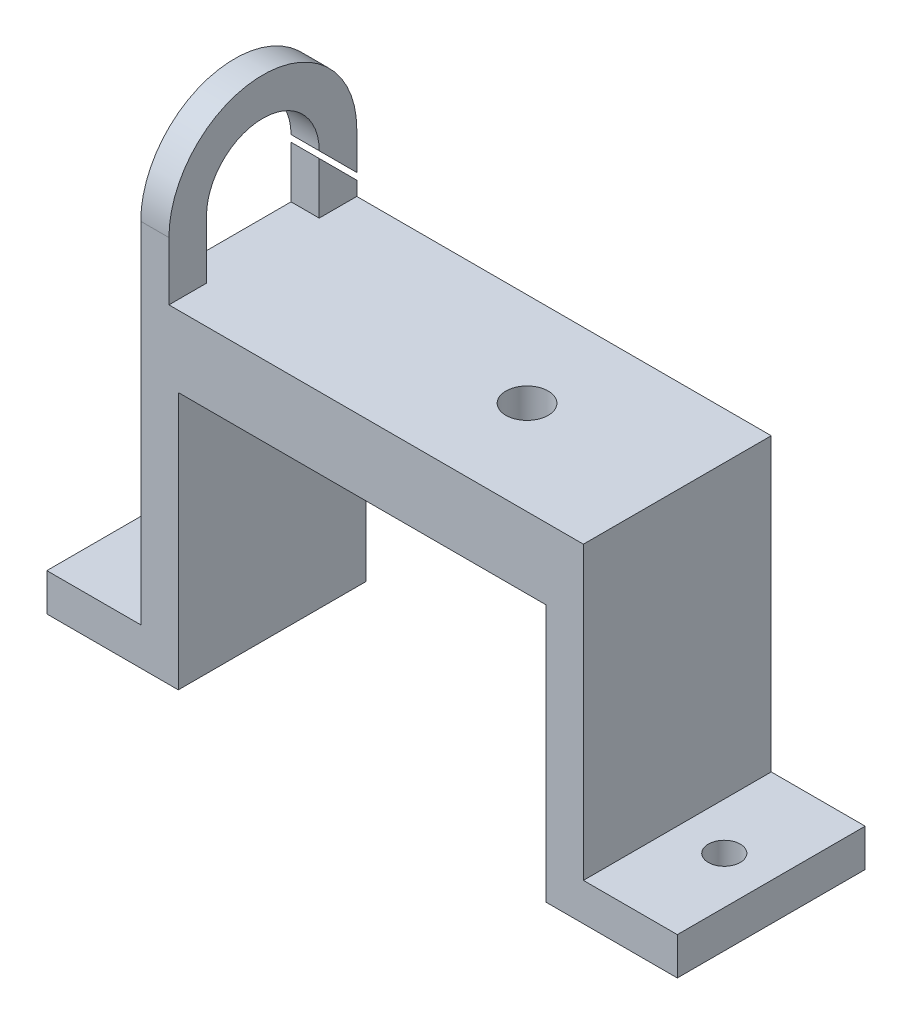
SolidWorks part; units mm, degrees
material "Onyx w/ CF"
ref_plane "Front Plane" through (0, 0, 0) normal (0, 0, 1) x (1, 0, 0)
ref_plane "Top Plane" through (0, 0, 0) normal (0, 1, 0) x (1, 0, 0)
ref_plane "Right Plane" through (0, 0, 0) normal (1, 0, 0) x (0, 0, -1)
sketch "Sketch1" plane through (0, 0, 0) normal (0, 0, 1) x (1, 0, 0)
  line L0 (-19.5635, 0) -> (19.5635, 0)
  line L1 (-19.5635, 0) -> (-19.5635, -31)
  line L2 (19.5635, 0) -> (19.5635, -31)
  line L3 (-19.5635, -31) -> (-33.5635, -31)
  line L4 (-33.5635, -31) -> (-33.5635, -27)
  line L5 (-33.5635, -27) -> (-23.5635, -27)
  line L6 (-23.5635, -27) -> (-23.5635, 4)
  line L7 (-23.5635, 4) -> (23.5635, 4)
  line L8 (23.5635, 4) -> (23.5635, -27)
  line L9 (23.5635, -27) -> (33.5635, -27)
  line L10 (33.5635, -27) -> (33.5635, -31)
  line L11 (33.5635, -31) -> (19.5635, -31)
  point P3 (0, 0)
  dimension "D1" = 39.127
  dimension "D2" = 31
  dimension "D3" = 4
  dimension "D4" = 4
  dimension "D5" = 10
  dimension "D6" = 4
extrude "Boss-Extrude1" add sketch "Sketch1" along normal mid plane 20
sketch "Sketch2" plane through (0, 0, 0) normal (1, 0, 0) x (0, 0, -1)
  line L0 (-10, 0) -> (10, 0) construction
  line L1 (-10, 4) -> (-10, -27) construction
  line L2 (10, 4) -> (10, -27) construction
  line L3 (-10, 0) -> (10, 0)
  line L4 (10, -3.5819) -> (10, 0)
  line L5 (-10, -3.5819) -> (-10, 0)
  arc A0 (-10, -3.5819) -> (10, -3.5819) centre (0, -15.75) cw
  dimension "D1" = 15.75
extrude "Boss-Extrude2" add sketch "Sketch2" along normal up to surface (39.127 mm away) from surface at -19.5635 contours L5 A0 L3 | L3 A0 L4 up to face at (19.5635, -15.5, 0) starting at face at (-19.5635, -15.5, 0)
hole_wizard "M3 Clearance Hole1" positions "Sketch3" profile "Sketch4" hole size "M3" standard "ANSI Metric"
sketch "Sketch3" plane through (0, -27, 0) normal (0, 1, 0) x (1, 0, 0)
  line L0 (-23.5635, 10) -> (-33.5635, 10) construction
  line L1 (33.5635, 10) -> (23.5635, 10) construction
  line L2 (33.5635, -10) -> (33.5635, 10) construction
  point P0 (28.5635, 0)
  point P2 (28.5635, 0)
  point P4 (-28.5635, 0)
  point P9 (-28.5635, 10)
  point P12 (28.5635, 10)
  point P15 (33.5635, 0)
sketch "Sketch4" plane through (28.5635, -27, 0) normal (1, 0, 0) x (0, 0, 1)
  line L0 (0, 0) -> (0, 8.5215)
  line L1 (0, 8.5215) -> (1.7, 7.5)
  line L2 (1.7, 7.5) -> (1.7, 0)
  line L5 (1.7, 0) -> (0, 0)
  line L10 (0, 8.5215) -> (-1.7, 7.5) construction
  line L11 (0, -6.35) -> (0, 107.95) construction
  dimension "Hole Dia." = 3.4
  dimension "Hole Depth" = 7.5
  dimension "Drill Angle" = 118
hole_wizard "M4 Clearance Hole1" positions "Sketch5" profile "Sketch6" hole size "M4" standard "ANSI Metric" end condition through all
sketch "Sketch5" plane through (0, 4, 0) normal (0, 1, 0) x (1, 0, 0)
  line L0 (19.5635, 10) -> (19.5635, -10) construction
  point P0 (7.5635, 0)
  dimension "D1" = 12
sketch "Sketch6" plane through (7.5635, 4, 0) normal (1, 0, 0) x (0, 0, 1)
  line L0 (0, 0) -> (0, 35)
  line L1 (0, 35) -> (2.25, 35)
  line L2 (2.25, 35) -> (2.25, 0)
  line L5 (2.25, 0) -> (0, 0)
  line L11 (0, -6.35) -> (0, 107.95) construction
  dimension "Thru Hole Dia." = 4.5
  dimension "Thru Hole Depth" = 35
sketch "Sketch7" plane through (-23.5635, 0, 0) normal (-1, 0, 0) x (0, 0, 1)
  line L0 (-10, 4) -> (-10, 5.5)
  line L1 (10, 4) -> (-10, 4) construction
  line L2 (-10, 5.5) -> (-6, 9.5)
  line L3 (-6, 9.5) -> (-6, 4)
  line L4 (-6, 4) -> (-10, 4)
  line L5 (-10, 6.2071) -> (-6, 10.2071)
  line L6 (10, 4) -> (10, 10.2071)
  line L7 (10, 4) -> (10, -27) construction
  line L8 (10, 4) -> (6, 4)
  line L9 (6, 4) -> (6, 10.2071)
  line L10 (-10, 6.2071) -> (-10, 10.2071)
  arc A0 (6, 10.2071) -> (-6, 10.2071) centre (0, 10.2071) ccw
  arc A1 (10, 10.2071) -> (-10, 10.2071) centre (0, 10.2071) ccw
  point P26 (0, 16.2071)
  point P27 (0, 20.2071)
  dimension "D3" = 0.5
  dimension "D1" = 4
  dimension "D2" = 45
  dimension "D4" = 4
  dimension "D5" = 1.5
extrude "Boss-Extrude3" add sketch "Sketch7" against normal blind 3
